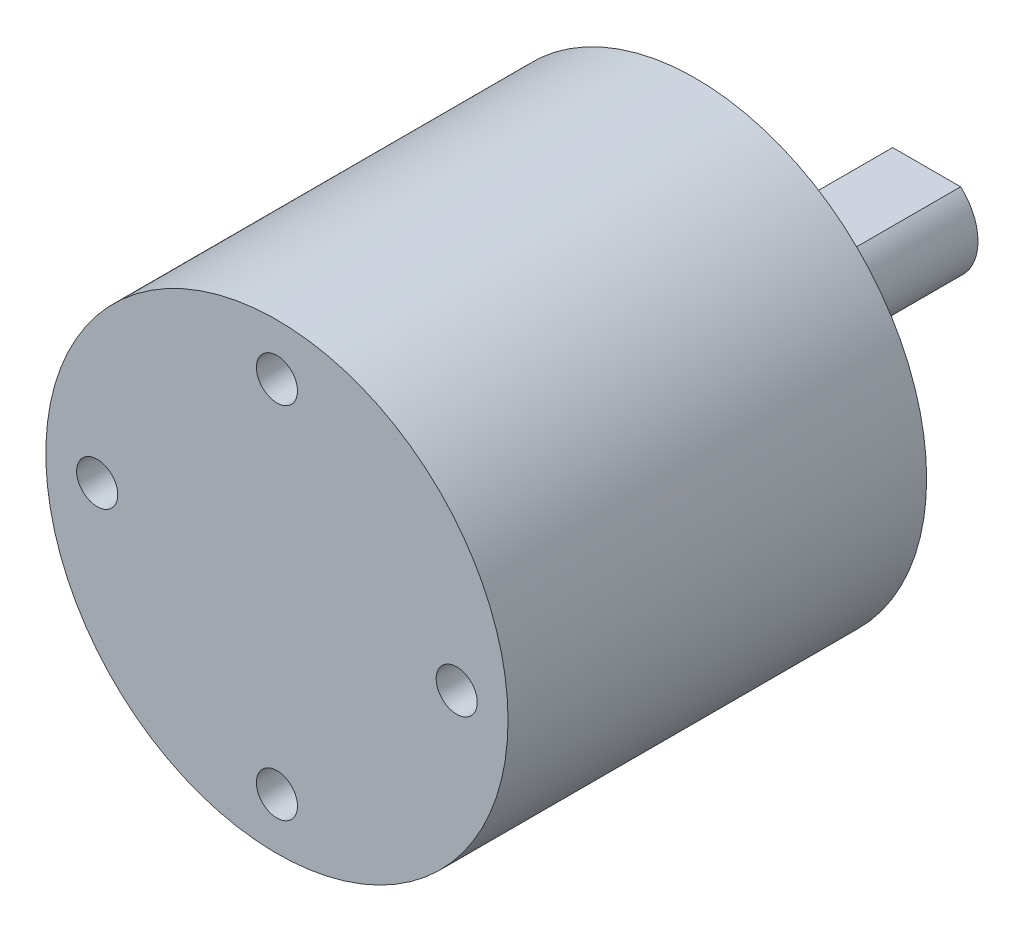
SolidWorks part; units mm, degrees
ref_plane "Front Plane" through (0, 0, 0) normal (0, 0, 1) x (1, 0, 0)
ref_plane "Top Plane" through (0, 0, 0) normal (0, 1, 0) x (1, 0, 0)
ref_plane "Right Plane" through (0, 0, 0) normal (1, 0, 0) x (0, 0, -1)
sketch "Sketch1" plane through (0, 0, 0) normal (0, 0, 1) x (1, 0, 0)
  circle A0 centre (0, 0) radius 18
  dimension "D1" = 36
extrude "Boss-Extrude1" add sketch "Sketch1" along normal blind 32.6
sketch "Sketch2" plane through (0, 0, 0) normal (0, 0, -1) x (-1, 0, 0)
  circle A0 centre (0, 0) radius 14 construction
  circle A1 centre (0, 14) radius 1.6
  dimension "D1" = 28
  dimension "D2" = 3.2
extrude "Cut-Extrude1" cut sketch "Sketch2" against normal through all
pattern_circular "CirPattern1" count 4 over 360 about axis through (0, 0, 0) along (0, 0, 1) of "Cut-Extrude1"
sketch "Sketch3" plane through (0, 0, 0) normal (0, 0, -1) x (-1, 0, 0)
  circle A0 centre (0, 0) radius 11
  dimension "D1" = 22
extrude "Boss-Extrude2" add sketch "Sketch3" along normal blind 2
sketch "Sketch4" plane through (0, 0, -2) normal (0, 0, -1) x (-1, 0, 0)
  circle A0 centre (0, 0) radius 4
  dimension "D1" = 8
extrude "Boss-Extrude3" add sketch "Sketch4" along normal blind 16
sketch "Sketch5" plane through (0, 0, -18) normal (0, 0, -1) x (-1, 0, 0)
  line L0 (-5, 3) -> (-2.6458, 3) construction
  line L1 (-2.6458, 3) -> (2.6458, 3)
  line L2 (-5, 3) -> (-5, -3) construction
  line L3 (-2.6458, -3) -> (2.6458, -3)
  line L4 (5, 3) -> (5, -3) construction
  line L5 (-5, 3) -> (5, -3) construction
  line L6 (-5, -3) -> (5, 3) construction
  line L7 (-5, -3) -> (-2.6458, -3) construction
  line L8 (2.6458, 3) -> (5, 3) construction
  line L9 (2.6458, -3) -> (5, -3) construction
  circle A0 centre (0, 0) radius 4 construction
  arc A1 (-3.43, 2.058) -> (-3.43, -2.058) centre (0, 0) ccw construction
  arc A2 (-2.6458, 3) -> (-3.43, 2.058) centre (0, 0) ccw construction
  arc A3 (-3.43, -2.058) -> (-2.6458, -3) centre (0, 0) ccw construction
  arc A4 (-2.6458, -3) -> (2.6458, -3) centre (0, 0) ccw
  arc A5 (2.6458, -3) -> (3.43, -2.058) centre (0, 0) ccw construction
  arc A6 (2.6458, 3) -> (-2.6458, 3) centre (0, 0) ccw
  arc A7 (3.43, -2.058) -> (3.43, 2.058) centre (0, 0) ccw construction
  arc A8 (3.43, 2.058) -> (2.6458, 3) centre (0, 0) ccw construction
  point P0 (0, 0)
  dimension "D1" = 6
  dimension "D2" = 10
extrude "Cut-Extrude2" cut sketch "Sketch5" against normal blind 15
